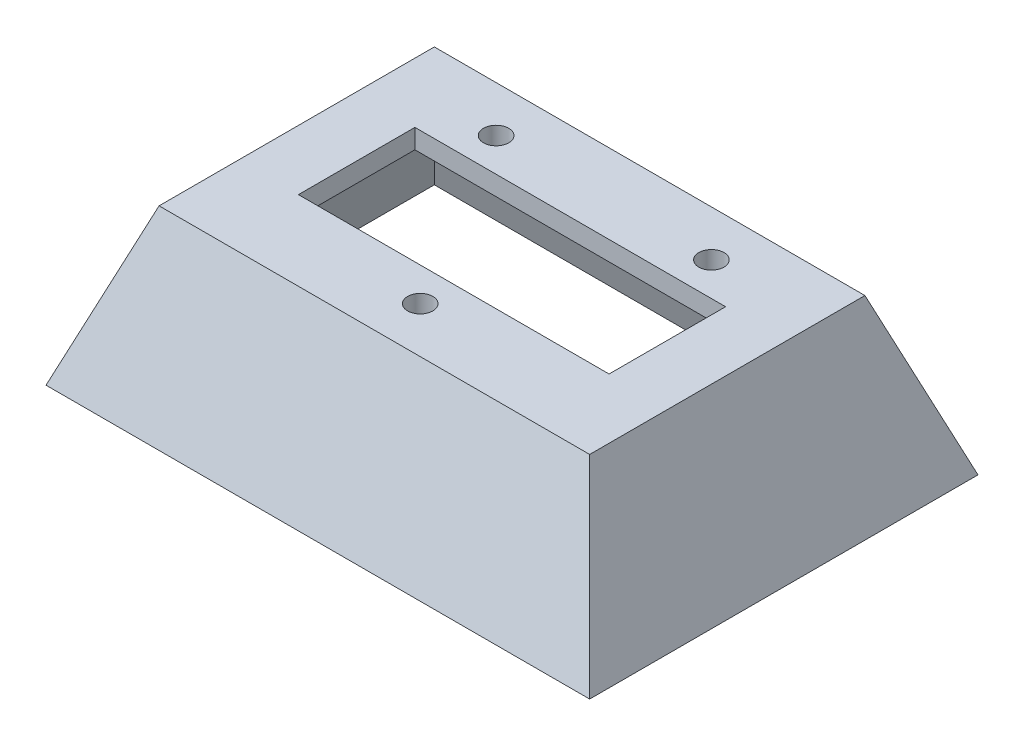
SolidWorks part; units mm, degrees
ref_plane "Front Plane" through (0, 0, 0) normal (0, 0, 1) x (1, 0, 0)
ref_plane "Top Plane" through (0, 0, 0) normal (0, 1, 0) x (1, 0, 0)
ref_plane "Right Plane" through (0, 0, 0) normal (1, 0, 0) x (0, 0, -1)
sketch "Sketch1" plane through (0, 0, 0) normal (0, 1, 0) x (1, 0, 0)
  line L1 (-70, -50) -> (70, -50)
  line L2 (-70, -50) -> (-70, 50)
  line L3 (-70, 50) -> (70, 50)
  line L4 (70, -50) -> (70, 50)
  line L5 (-70, -50) -> (70, 50) construction
  line L6 (-70, 50) -> (70, -50) construction
  point P0 (0, 0)
  point P6 (0, 0)
  dimension "D1" = 140
  dimension "D2" = 100
extrude "Boss-Extrude2" add sketch "Sketch1" along normal blind 40 draft 20
shell "Shell1" thickness 5
sketch "Sketch3" plane through (0, 40, 0) normal (0, 1, 0) x (1, 0, 0)
  line L0 (-55.4412, 0) -> (55.4412, 0) construction
  line L1 (55.4412, -35.4412) -> (55.4412, 35.4412) construction
  line L2 (0, 106.3236) -> (0, -35.4412) construction
  line L3 (55.4412, 0) -> (55.4412, -35.4412) construction
  line L4 (-55.4412, -35.4412) -> (55.4412, -35.4412) construction
  line L6 (-55.4412, 0) -> (-55.4412, -35.4412) construction
  line L7 (55.4412, 35.4412) -> (-55.4412, 35.4412) construction
  line L8 (0, 35.4412) -> (0, 0) construction
  line L9 (-55.4412, 23.6312) -> (0, 23.6312) construction
  line L10 (0, 23.6312) -> (55.4412, 23.6312) construction
  line L11 (-36.5, 0) -> (36.5, 0)
  line L13 (-55.4412, 35.4412) -> (-55.4412, 23.6312) construction
  line L14 (-40, -15) -> (40, -15)
  line L15 (-40, -15) -> (-40, 15)
  line L16 (-40, 15) -> (40, 15)
  line L17 (40, -15) -> (40, 15)
  line L18 (-40, -15) -> (40, 15) construction
  line L19 (-40, 15) -> (40, -15) construction
  circle A0 centre (0, -23.6312) radius 3.25
  circle A1 centre (-27.7206, 23.6312) radius 3.25
  circle A2 centre (27.7206, 23.6312) radius 3.25
  point P6 (0, 0)
  point P10 (0, 35.4412)
  point P32 (0, 0)
  point P37 (0, 0)
  point P38 (0, 0)
  point P39 (0, 0)
  point P40 (0, 0)
  point P41 (0, 0)
  dimension "D1" = 6.5
  dimension "D2" = 6.5
  dimension "D3" = 6.5
  dimension "D4" = 73
  dimension "D5" = 11.81
  dimension "D6" = 11.81
  dimension "D7" = 30
  dimension "D8" = 80
extrude "Cut-Extrude1" cut sketch "Sketch3" against normal through all
